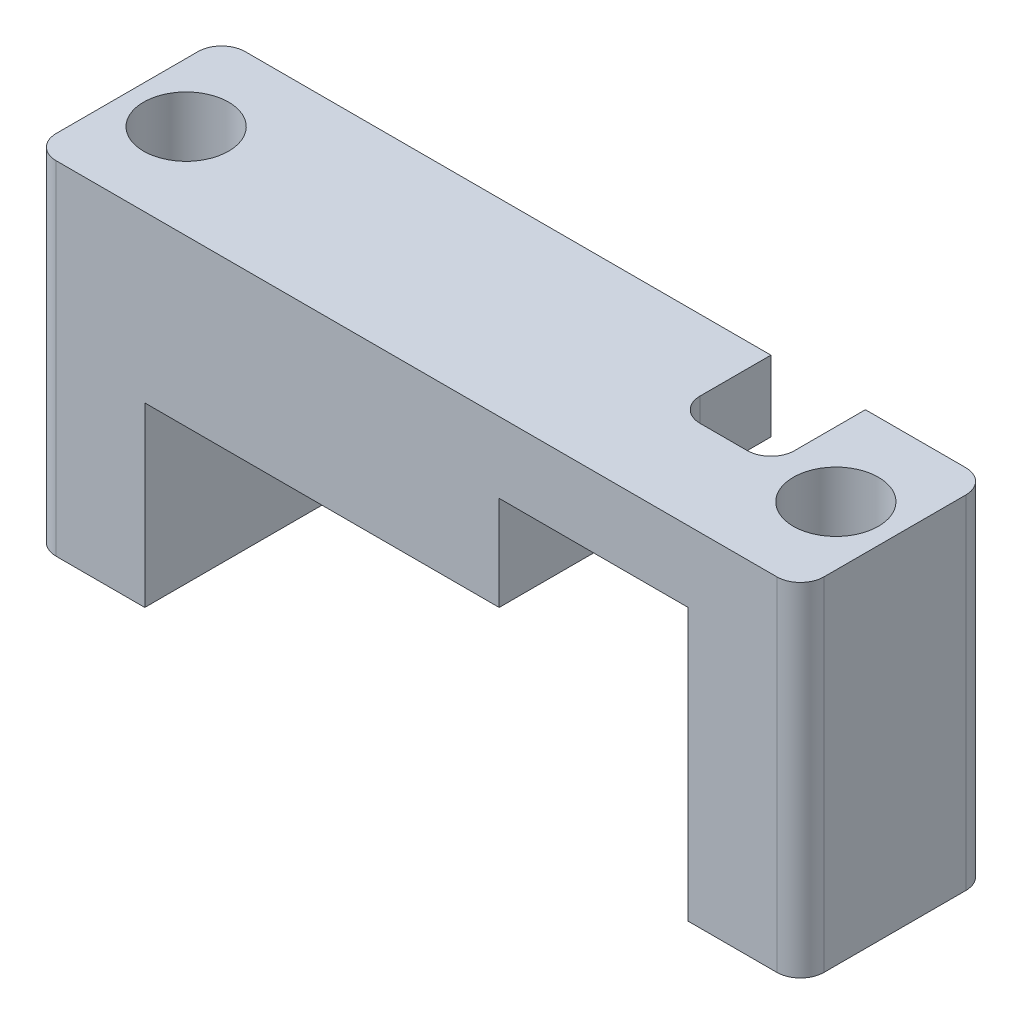
SolidWorks part; units mm, degrees
ref_plane "Front Plane" through (0, 0, 0) normal (0, 0, 1) x (1, 0, 0)
ref_plane "Top Plane" through (0, 0, 0) normal (0, 1, 0) x (1, 0, 0)
ref_plane "Right Plane" through (0, 0, 0) normal (1, 0, 0) x (0, 0, -1)
sketch "Sketch1" plane through (0, 0, 0) normal (0, 0, 1) x (1, 0, 0)
  line L0 (-16.25, -7.5) -> (-11.5, -7.5)
  line L1 (-11.5, -7.5) -> (-11.5, 0)
  line L2 (-11.5, 0) -> (3.5, 0)
  line L3 (3.5, 0) -> (3.5, 4)
  line L4 (3.5, 4) -> (11.5, 4)
  line L5 (11.5, 4) -> (11.5, -7.5)
  line L6 (11.5, -7.5) -> (16.25, -7.5)
  line L7 (16.25, -7.5) -> (16.25, 7)
  line L8 (16.25, 7) -> (-16.25, 7)
  line L9 (-16.25, 7) -> (-16.25, -7.5)
  point P10 (0, 7)
  dimension "D1" = 23
  dimension "D2" = 32.5
  dimension "D3" = 3.5
  dimension "D4" = 4
  dimension "D5" = 7.5
  dimension "D6" = 3
extrude "Boss-Extrude1" add sketch "Sketch1" along normal blind 8 contours L8 L9 L0 L1 L2 L3 L4 L5 L6 L7
hole_wizard "M3 Clearance Hole1" positions "Sketch2" profile "Sketch4" hole size "M3" standard "ISO" end condition up to next
sketch "Sketch2" plane through (0, 7, 0) normal (0, 1, 0) x (1, 0, 0)
  line L0 (-16.25, -8) -> (-16.25, 0) construction
  line L1 (13.75, -4) -> (-13.75, -4)
  line L3 (16.25, 0) -> (-16.25, 0) construction
  point P0 (13.75, -4)
  point P2 (-13.75, -4)
  point P7 (-16.25, -4)
  point P12 (0, -4)
  point P15 (0, 0)
  dimension "D1" = 27.5
sketch "Sketch4" plane through (13.75, 7, 4) normal (1, 0, 0) x (0, 0, 1)
  line L0 (0, 0) -> (0, 14.5)
  line L1 (0, 14.5) -> (1.8, 14.5)
  line L2 (1.8, 14.5) -> (1.8, 0)
  line L5 (1.8, 0) -> (0, 0)
  line L11 (0, -6.35) -> (0, 107.95) construction
  dimension "Thru Hole Dia." = 3.6
  dimension "Thru Hole Depth" = 14.5
fillet "Fillet1" radius 1 4 edges at (16.25, -0.25, 0) (16.25, -0.25, 8) (-16.25, -0.25, 0) (-16.25, -0.25, 8)
sketch "Sketch5" plane through (0, 0, 0) normal (0, 0, -1) x (-1, 0, 0)
  line L0 (-15.25, 7) -> (15.25, 7) construction
  line L1 (-11, 7) -> (-7, 7)
  line L2 (-11, 7) -> (-11, 0)
  line L3 (-11, 0) -> (-7, 0)
  line L4 (-7, 7) -> (-7, 0)
  line L6 (11.5, 0) -> (-3.5, 0) construction
  line L9 (-11.5, 4) -> (-11.5, -7.5) construction
  dimension "D1" = 4
  dimension "D2" = 0.5
extrude "Cut-Extrude1" cut sketch "Sketch5" against normal blind 4
fillet "Fillet2" radius 1 2 edges at (11, 5.5, 4) (7, 5.5, 4)
other "Freeze***"
